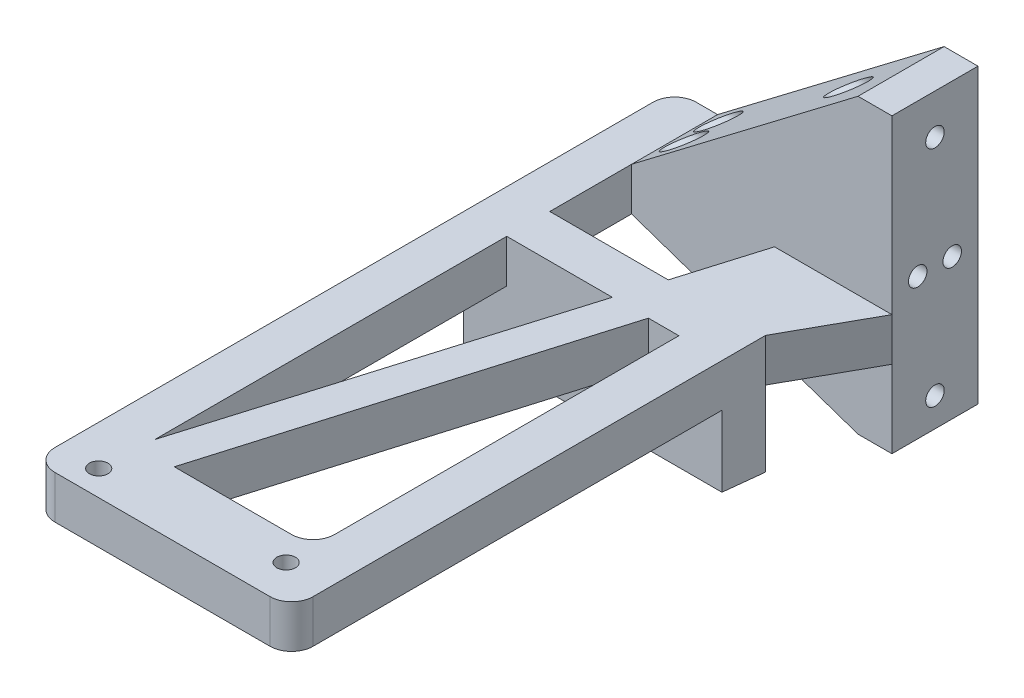
SolidWorks part; units mm, degrees
ref_plane "前视基准面" through (0, 0, 0) normal (0, 0, 1) x (1, 0, 0)
ref_plane "上视基准面" through (0, 0, 0) normal (0, 1, 0) x (1, 0, 0)
ref_plane "右视基准面" through (0, 0, 0) normal (1, 0, 0) x (0, 0, -1)
sketch "草图1" plane through (0, 0, 0) normal (0, 1, 0) x (1, 0, 0)
  line L0 (5.9312, 81.5722) -> (53.1808, 81.5722)
  line L1 (-17.3192, 81.5722) -> (5.9312, 81.5722)
  line L2 (-17.3192, 81.5722) -> (-17.3192, -67.4278)
  line L3 (-17.3192, -67.4278) -> (0.4312, -67.4278)
  line L7 (53.1808, 81.5722) -> (53.1808, 61.5722)
  line L12 (42.6808, -57.6007) -> (42.6808, -67.4278)
  line L13 (42.6808, -67.4278) -> (0.4312, -67.4278)
  line L15 (42.6808, -57.6007) -> (42.6808, 31.7573)
  line L17 (47.9308, 61.5722) -> (42.6808, 61.5722)
  line L18 (42.6808, 61.5722) -> (42.6808, 52.6895)
  line L19 (25.9063, 61.5722) -> (-7.3192, 61.5722)
  line L21 (0.4312, -52.4278) -> (32.6808, -52.4278)
  line L22 (32.6808, -52.4278) -> (32.6808, 56.5081)
  line L23 (-7.3192, 61.5722) -> (-7.3192, -49.2207)
  line L24 (25.9063, 61.5722) -> (-7.3192, -49.2207)
  line L25 (32.6808, 56.5081) -> (0.4312, -52.4278)
  line L26 (47.9308, 61.5722) -> (42.6808, 52.6895)
  line L27 (53.1808, 61.5722) -> (42.6808, 42.721)
  line L28 (42.6808, 42.721) -> (42.6808, 31.7573)
  point P0 (0, 0)
  dimension "D1" = 149
  dimension "D2" = 60
  dimension "D3" = 70.5
  dimension "D4" = 10
  dimension "D5" = 10
  dimension "D6" = 15
  dimension "D7" = 20
extrude "凸台-拉伸1" add sketch "草图1" along normal blind 10
sketch "草图4" plane through (0, 10, 0) normal (0, 1, 0) x (1, 0, 0)
  line L0 (45.3058, 81.5722) -> (45.3058, 61.5722)
  line L1 (53.1808, 81.5722) -> (-17.3192, 81.5722) construction
  line L2 (42.6808, 61.5722) -> (47.9308, 61.5722) construction
  line L3 (45.3058, 61.5722) -> (53.1808, 61.5722)
  line L4 (53.1808, 61.5722) -> (53.1808, 81.5722)
  line L5 (53.1808, 81.5722) -> (45.3058, 81.5722)
  line L7 (53.1808, 61.5722) -> (53.1808, 81.5722) construction
extrude "凸台-拉伸2" add sketch "草图4" along normal blind 40
sketch "草图5" plane through (45.3058, 0, 0) normal (-1, 0, 0) x (0, 0, 1)
  line L0 (-75.5722, 14.7) -> (-60.9452, 14.7) construction
  line L1 (-71.5722, 50) -> (-71.5722, 5.7819) construction
  line L2 (-81.5722, 50) -> (-61.5722, 50) construction
  line L3 (-81.5722, 10) -> (-61.5722, 10) construction
  circle A0 centre (-75.5722, 14.7) radius 2.15
  circle A1 centre (-67.5722, 14.7) radius 2.15
  circle A2 centre (-71.5722, 40.7) radius 2.15
  dimension "D2" = 4.3
  dimension "D3" = 4.3
  dimension "D5" = 4.3
  dimension "D1" = 8
  dimension "D4" = 4
  dimension "D6" = 26
  dimension "D7" = 4.7
extrude "切除-拉伸1" cut sketch "草图5" against normal up to next and the other way blind 53
sketch "草图6" plane through (0, 10, 0) normal (0, 1, 0) x (1, 0, 0)
  line L0 (32.8487, -73.9107) -> (32.6808, -58.6926) construction
  line L1 (32.6808, -52.4278) -> (32.6808, 56.5081) construction
  line L2 (-25.0369, -58.6926) -> (44.4062, -58.6926) construction
  circle A0 centre (-8.0192, -61.5426) radius 2.15
  circle A1 centre (32.6808, -58.6926) radius 2.15
  dimension "D1" = 4.3
  dimension "D2" = 4.3
  dimension "D3" = 40.7
  dimension "D4" = 2.85
extrude "切除-拉伸2" cut sketch "草图6" against normal up to next
fillet "圆角1" radius 5 3 edges at (-17.3192, 5, -81.5722) (42.6808, 5, 67.4278) (-17.3192, 5, 67.4278)
fillet "圆角2" radius 5 1 edges at (32.6808, 5, 52.4278)
sketch "草图7" plane through (0, 0, 0) normal (0, -1, 0) x (1, 0, 0)
  line L0 (53.1808, -61.5722) -> (53.1808, -81.5722)
  line L1 (53.1808, -81.5722) -> (45.3058, -81.5722)
  line L2 (53.1808, -81.5722) -> (-12.3192, -81.5722) construction
  line L3 (45.3058, -81.5722) -> (45.3058, -61.5722)
  line L4 (45.3058, -61.5722) -> (53.1808, -61.5722)
  dimension "D1" = 7.875
extrude "凸台-拉伸3" add sketch "草图7" along normal blind 18
sketch "草图8" plane through (45.3058, 0, 0) normal (-1, 0, 0) x (0, 0, 1)
  line L0 (-71.5722, -18) -> (-71.5722, 20.1583) construction
  line L1 (-61.5722, -18) -> (-81.5722, -18) construction
  line L2 (-61.5722, 0) -> (-81.5722, 0) construction
  circle A0 centre (-71.5722, -11.3) radius 2.15
  dimension "D1" = 4.3
  dimension "D2" = 11.3
extrude "切除-拉伸3" cut sketch "草图8" against normal up to next
sketch "草图13" plane through (0, 0, -61.5722) normal (0, 0, 1) x (1, 0, 0)
  line L3 (45.3058, 0) -> (45.3058, -18)
  line L4 (45.3058, -18) -> (-7.3192, 0)
  line L5 (-7.3192, 0) -> (45.3058, 0)
sketch "草图14" plane through (53.1808, 0, 0) normal (1, 0, 0) x (0, 0, -1)
  circle A0 centre (71.5722, 40.7) radius 3.5
  circle A1 centre (67.5722, 14.7) radius 3.5
  circle A2 centre (75.5722, 14.7) radius 3.5
  circle A3 centre (71.5722, -11.3) radius 3.5
  dimension "D1" = 7
  dimension "D2" = 7
  dimension "D3" = 7
  dimension "D4" = 7
extrude "凸台-拉伸8" add sketch "草图13" against normal blind 20
sketch "草图15" plane through (0, 10, 0) normal (0, 1, 0) x (1, 0, 0)
  line L1 (45.3058, 81.5722) -> (-7.3192, 81.5722)
  line L2 (45.3058, 81.5722) -> (45.3058, 61.5722)
  line L3 (45.3058, 61.5722) -> (-7.3192, 61.5722)
  line L4 (-7.3192, 81.5722) -> (-7.3192, 61.5722)
extrude "凸台-拉伸9" add sketch "草图15" along normal blind 40
extrude "切除-拉伸8" cut sketch "草图14" against normal blind 54 from offset 7.875 offset against normal yes
sketch "草图17" plane through (0, 0, -61.5722) normal (0, 0, 1) x (1, 0, 0)
  line L1 (-7.3192, 50) -> (53.1808, 50) construction
  line L6 (-7.3192, 10) -> (-7.3192, 50)
  line L7 (-7.3192, 50) -> (45.3058, 50)
  line L8 (45.3058, 50) -> (-7.3192, 10)
  line L9 (53.1808, 50) -> (53.1808, 10) construction
  dimension "D1" = 7.875
extrude "切除-拉伸10" cut sketch "草图17" against normal blind 20
sketch "草图18" plane through (0, 10, 0) normal (0, 1, 0) x (1, 0, 0)
  line L0 (-7.3192, 32.5722) -> (17.2095, 32.5722)
  line L1 (-7.3192, 61.5722) -> (-7.3192, -49.2207) construction
  line L2 (-7.3192, -49.2207) -> (25.9063, 61.5722) construction
  line L3 (-12.3192, -67.4278) -> (37.6808, -67.4278) construction
  line L4 (-7.3192, 42.5722) -> (20.2084, 42.5722)
  line L5 (-7.3192, 42.5722) -> (-7.3192, 32.5722)
  line L6 (20.2084, 42.5722) -> (17.2095, 32.5722)
  line L7 (25.5947, 32.5722) -> (32.6808, 32.5722)
  line L8 (32.6808, 56.5081) -> (0.4312, -52.4278) construction
  line L9 (32.6808, -47.4278) -> (32.6808, 56.5081) construction
  line L10 (32.6808, 32.5722) -> (32.6808, 56.5081)
  line L11 (32.6808, 56.5081) -> (25.5947, 32.5722)
  line L12 (42.6808, 61.5722) -> (42.6808, 52.6895)
  line L13 (42.6808, 52.6895) -> (47.9308, 61.5722)
  line L14 (47.9308, 61.5722) -> (42.6808, 61.5722)
  dimension "D1" = 100
  dimension "D2" = 10
extrude "凸台-拉伸10" add sketch "草图18" against normal blind 10
sketch "草图19" plane through (0, 0, 0) normal (0, -1, 0) x (1, 0, 0)
  line L0 (0, -42.5722) -> (-29.7395, -42.5722) construction
  line L1 (20.2084, -42.5722) -> (-7.3192, -42.5722) construction
  line L2 (-2.6209, -32.5722) -> (-42.0853, -32.5722) construction
  line L3 (-7.3192, -32.5722) -> (17.2095, -32.5722) construction
  line L4 (-17.3192, -32.5722) -> (-17.3192, -42.5722)
  line L5 (-17.3192, -76.5722) -> (-17.3192, 62.4278) construction
  line L6 (-17.3192, -42.5722) -> (42.6808, -42.721)
  line L7 (42.6808, -42.721) -> (42.6808, -32.5722)
  line L8 (42.6808, 62.4278) -> (42.6808, -42.721) construction
  line L9 (42.6808, -32.5722) -> (-17.3192, -32.5722)
extrude "凸台-拉伸11" add sketch "草图19" along normal blind 17.5
sketch "草图20" plane through (-17.3192, 0, 0) normal (-1, 0, 0) x (0, 0, 1)
  line L0 (-42.5722, -17.5) -> (-32.5722, -17.5)
  line L1 (-32.5722, -17.5) -> (-32.5722, -16.5)
  line L2 (-32.5722, -17.5) -> (-32.5722, 0) construction
  line L3 (-32.5722, -16.5) -> (-42.5722, -17.5)
  dimension "D1" = 1
extrude "切除-拉伸11" cut sketch "草图20" against normal blind 64
